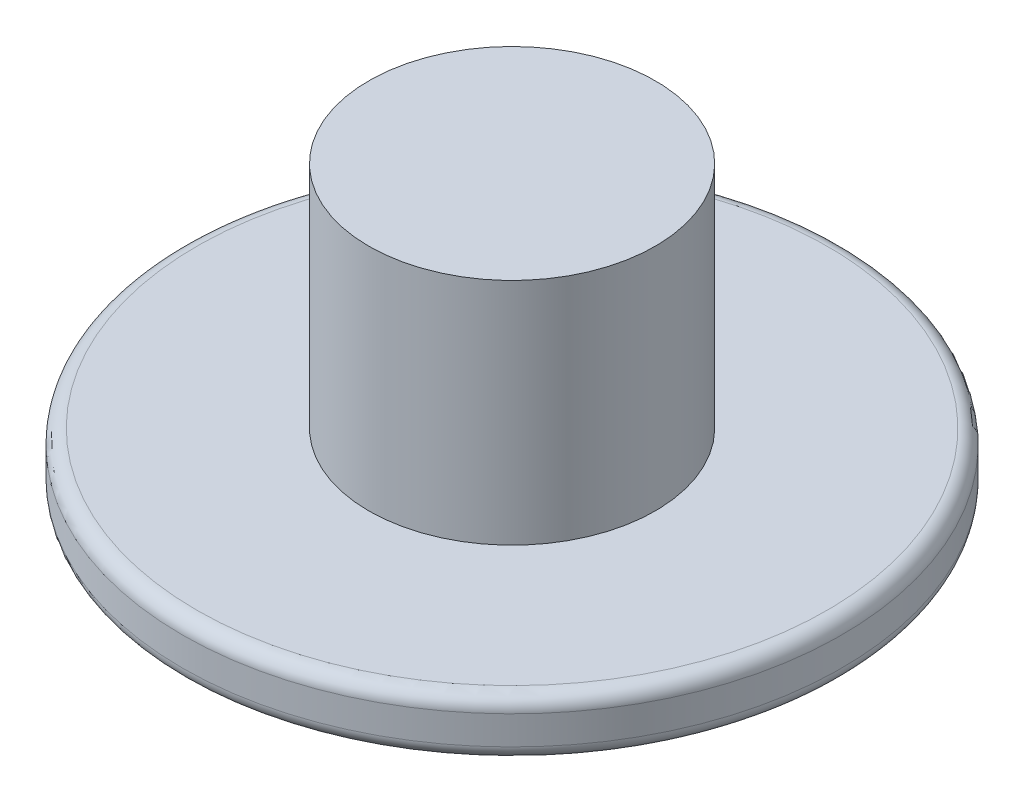
SolidWorks part; units mm, degrees
ref_plane "Front Plane" through (0, 0, 0) normal (0, 0, 1) x (1, 0, 0)
ref_plane "Top Plane" through (0, 0, 0) normal (0, 1, 0) x (1, 0, 0)
ref_plane "Right Plane" through (0, 0, 0) normal (1, 0, 0) x (0, 0, -1)
sketch "Sketch1" plane through (0, 0, 0) normal (0, 1, 0) x (1, 0, 0)
  circle A4 centre (-5.4087, -40.3067) radius 11.5
  circle A12 centre (-5.4087, -40.3067) radius 4.9321
  dimension "D5" = 23
extrude "Boss-Extrude5" add sketch "Sketch1" along normal blind 2 contours A4
sketch "Sketch4" plane through (0, 2, 0) normal (0, 1, 0) x (1, 0, 0)
  circle A0 centre (-5.4087, -40.3067) radius 5
  circle A1 centre (-5.4087, -40.3067) radius 11.5 construction
extrude "Boss-Extrude6" add sketch "Sketch4" along normal blind 8
sketch "Sketch5" plane through (0, 0, 0) normal (0, -1, 0) x (1, 0, 0)
  text T0 "10" font "DejaVu Sans" height 10
extrude "Cut-Extrude2" cut sketch "Sketch5" against normal blind 0.5
fillet "Fillet1" radius 0.5 2 edges at (-5.4087, 2, 51.8067) (-5.4087, 0, 51.8067)
